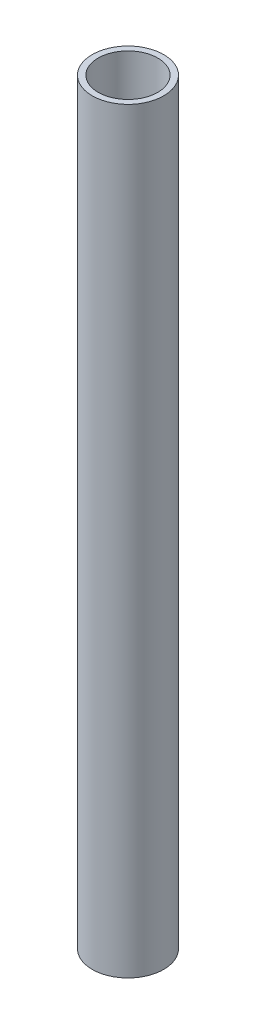
SolidWorks part; units mm, degrees
ref_plane "Front Plane" through (0, 0, 0) normal (0, 0, 1) x (1, 0, 0)
ref_plane "Top Plane" through (0, 0, 0) normal (0, 1, 0) x (1, 0, 0)
ref_plane "Right Plane" through (0, 0, 0) normal (1, 0, 0) x (0, 0, -1)
sketch "Sketch1" plane through (0, 0, 0) normal (0, 1, 0) x (1, 0, 0)
  circle A0 centre (0, 0) radius 5
  circle A1 centre (0, 0) radius 6
  dimension "D1" = 10
  dimension "D2" = 12
extrude "Boss-Extrude1" add sketch "Sketch1" along normal blind 127
